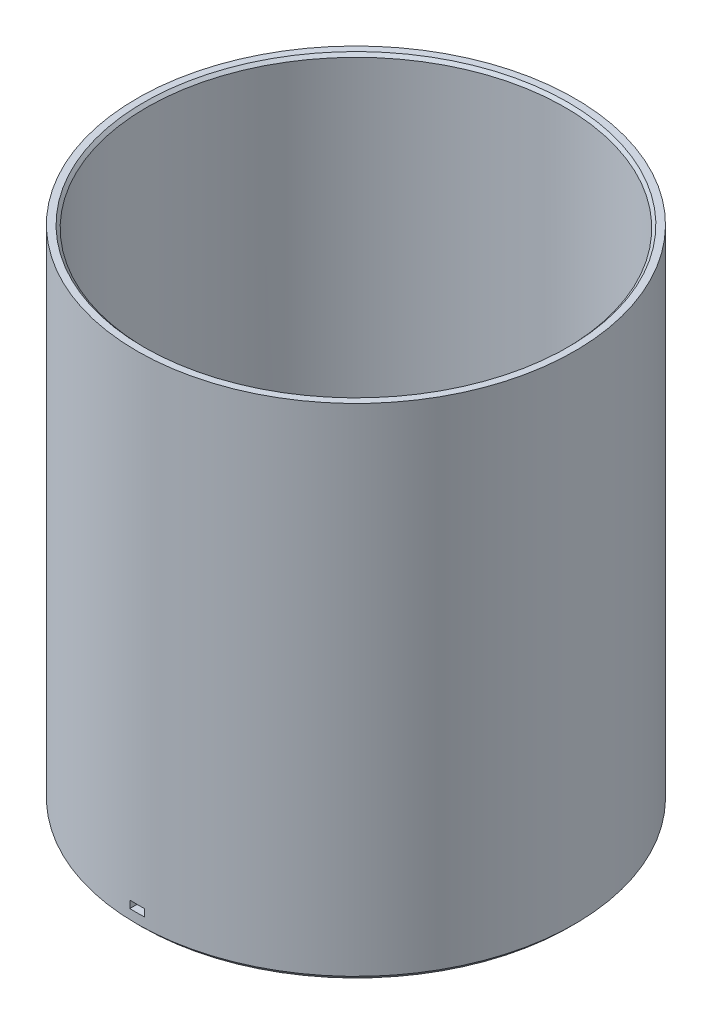
SolidWorks part; units mm, degrees
ref_plane "Front Plane" through (0, 0, 0) normal (0, 0, 1) x (1, 0, 0)
ref_plane "Top Plane" through (0, 0, 0) normal (0, 1, 0) x (1, 0, 0)
ref_plane "Right Plane" through (0, 0, 0) normal (1, 0, 0) x (0, 0, -1)
sketch "Sketch1" plane through (0, 0, 0) normal (0, 1, 0) x (1, 0, 0)
  circle A0 centre (0, 0) radius 45
  dimension "D1" = 90
extrude "Boss-Extrude1" add sketch "Sketch1" along normal blind 3
sketch "Sketch2" plane through (0, 3, 0) normal (0, 1, 0) x (1, 0, 0)
  circle A0 centre (0, 0) radius 43
  circle A1 centre (0, 0) radius 45
  circle A2 centre (0, 0) radius 45
  dimension "D1" = 0
  dimension "D2" = 2
extrude "Boss-Extrude2" add sketch "Sketch2" along normal blind 100
sketch "Sketch3" plane through (0, 3, 0) normal (0, 1, 0) x (1, 0, 0)
  line L0 (0, -15.25) -> (0, -17.25) construction
  line L1 (-1.5, -15.1761) -> (-1.5, -17.1847)
  line L2 (1.5, -15.1761) -> (1.5, -17.1847)
  arc A0 (1.5, -15.1761) -> (-1.5, -15.1761) centre (0, 0) ccw
  arc A1 (1.5, -17.1847) -> (-1.5, -17.1847) centre (0, 0) ccw
  circle A2 centre (0, 0) radius 15.25 construction
  circle A3 centre (0, 0) radius 17.25 construction
  dimension "D1" = 30.5
  dimension "D3" = 3
  dimension "D2" = 2
extrude "Boss-Extrude3" add sketch "Sketch3" along normal blind 5
ref_plane "Plane1" through (0, 0, 45) normal (0, 0, 1) x (1, 0, 0)
sketch "Sketch4" plane through (0, 0, 45) normal (0, 0, 1) x (1, 0, 0)
  line L0 (0, 0) -> (0, 21.0078) construction
  line L1 (-45, 0) -> (45, 0) construction
  line L2 (-1.5, 4.5) -> (1.5, 4.5)
  line L3 (-1.5, 4.5) -> (-1.5, 3)
  line L4 (-1.5, 3) -> (1.5, 3)
  line L5 (1.5, 4.5) -> (1.5, 3)
  line L6 (-1.5, 4.5) -> (1.5, 3) construction
  line L7 (-1.5, 3) -> (1.5, 4.5) construction
  point P3 (0, 3.75)
  dimension "D1" = 3
  dimension "D2" = 1.5
  dimension "D3" = 3
extrude "Cut-Extrude1" cut sketch "Sketch4" against normal blind 5
chamfer "Chamfer1" distance 0.6 angle 45 1 edges at (0, 103, 43)
chamfer "Chamfer2" distance 1 angle 45 1 edges at (0, 0, 45)
